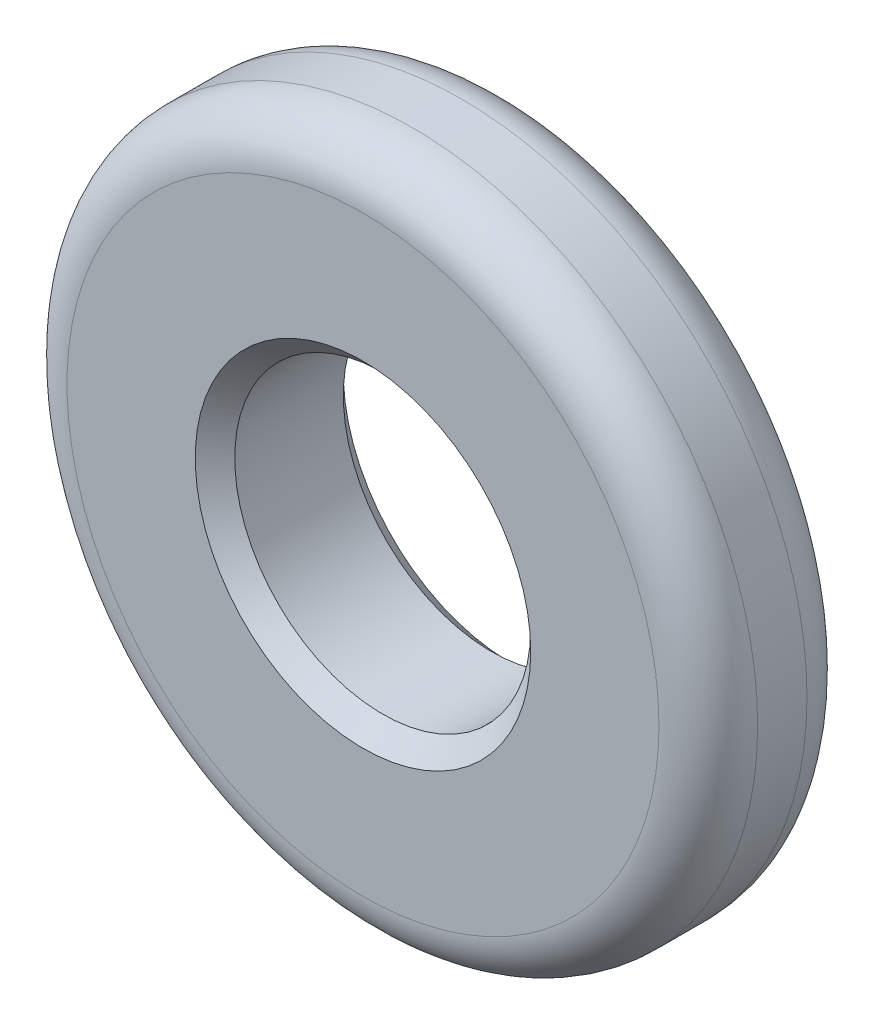
SolidWorks part; units mm, degrees
ref_plane "前视基准面" through (0, 0, 0) normal (0, 0, 1) x (1, 0, 0)
ref_plane "上视基准面" through (0, 0, 0) normal (0, 1, 0) x (1, 0, 0)
ref_plane "右视基准面" through (0, 0, 0) normal (1, 0, 0) x (0, 0, -1)
sketch "草图1" plane through (0, 0, 0) normal (0, 0, 1) x (1, 0, 0)
  circle A0 centre (0, 0) radius 35
  circle A1 centre (0, 0) radius 15
  dimension "D1" = 70
  dimension "D2" = 30
extrude "凸台-拉伸1" add sketch "草图1" along normal mid plane 15 contours A0
fillet "圆角1" radius 5 1 edges at (35, 0, 7.5)
fillet "圆角2" radius 5 1 edges at (35, 0, -7.5)
sketch "草图2" plane through (0, 0, 7.5) normal (0, 0, 1) x (1, 0, 0)
  circle A0 centre (0, 0) radius 15
  dimension "D1" = 30
extrude "切除-拉伸1" cut sketch "草图2" against normal blind 15
chamfer "倒角1" distance 2 angle 45 1 edges at (15, 0, 7.5)
chamfer "倒角2" distance 2 angle 45 1 edges at (15, 0, -7.5)
scale "缩放比例1" scale about origin uniform scaling yes scale factor 0.6
